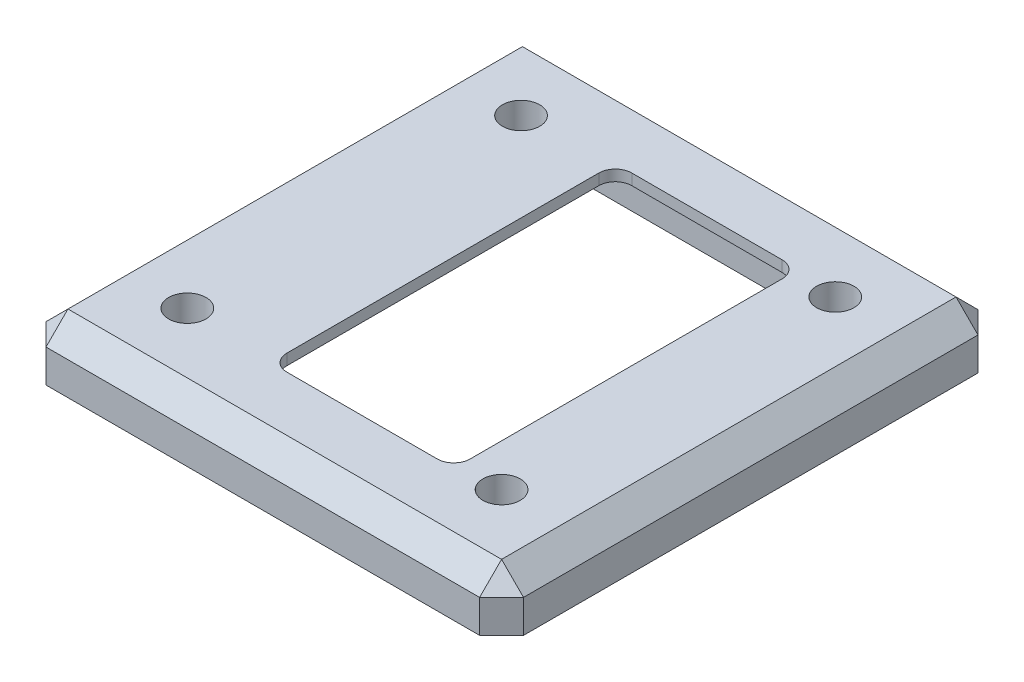
SolidWorks part; units mm, degrees
ref_plane "Спереди" through (0, 0, 0) normal (0, 0, 1) x (1, 0, 0)
ref_plane "Сверху" through (0, 0, 0) normal (0, 1, 0) x (1, 0, 0)
ref_plane "Справа" through (0, 0, 0) normal (1, 0, 0) x (0, 0, -1)
sketch "Эскиз2" plane through (0, 0, 0) normal (0, 1, 0) x (1, 0, 0)
  line L0 (-21.75, -7) -> (-21.75, -22.7)
  line L1 (-21.75, -22.7) -> (21.75, -22.7)
  line L2 (21.75, -22.7) -> (21.75, 22.7)
  line L3 (21.75, 22.7) -> (-21.75, 22.7)
  line L4 (-21.75, 22.7) -> (-21.75, 7)
  line L5 (-21.75, 11.7) -> (-21.75, -11.7)
  line L8 (16.75, 17.7) -> (-16.75, 17.7) construction
  line L9 (16.75, -17.7) -> (16.75, 17.7) construction
  line L10 (-16.75, -17.7) -> (16.75, -17.7) construction
  line L11 (-16.75, -7) -> (-16.75, -17.7) construction
  line L12 (-16.75, 17.7) -> (-16.75, 7) construction
  line L17 (-16.75, 11.7) -> (-16.75, -11.7) construction
  line L19 (16.75, 17.7) -> (-16.75, 17.7)
  line L20 (16.75, -17.7) -> (16.75, 17.7)
  line L21 (-16.75, -17.7) -> (16.75, -17.7)
  line L22 (-16.75, -7) -> (-16.75, -17.7)
  line L23 (-16.75, 17.7) -> (-16.75, 7)
  line L24 (-16.75, 11.7) -> (-16.75, -11.7)
  dimension "D1" = 5
extrude "Бобышка-Вытянуть2" add sketch "Эскиз2" along normal blind 5 contours L4 L5 L0 L1 L2 L3 L24 L23 L19 L20 L21 L22
sketch "Эскиз3" plane through (0, 5, 0) normal (0, 1, 0) x (1, 0, 0)
  line L0 (-13.0019, 12.7) -> (-15.75, 12.7) construction
  line L1 (-12.0019, -13.7) -> (-12.0019, -16.7) construction
  line L2 (-15.75, -12.7) -> (-13.0019, -12.7) construction
  line L3 (12.75, -12.7) -> (15.75, -12.7) construction
  line L4 (11.75, -16.7) -> (11.75, -13.7) construction
  line L5 (-16.75, -17.7) -> (16.75, -17.7) construction
  line L6 (16.75, -17.7) -> (16.75, 17.7) construction
  line L7 (15.75, 12.7) -> (12.75, 12.7) construction
  line L8 (11.75, 13.7) -> (11.75, 16.7) construction
  line L9 (-16.75, 17.7) -> (-16.75, -17.7) construction
  line L10 (16.75, 17.7) -> (-16.75, 17.7) construction
  line L11 (-12.0019, 16.7) -> (-12.0019, 13.7) construction
  line L12 (-12.0019, -13.7) -> (-12.0019, -16.7)
  line L13 (-15.75, -12.7) -> (-13.0019, -12.7)
  line L14 (12.75, -12.7) -> (15.75, -12.7)
  line L15 (11.75, -16.7) -> (11.75, -13.7)
  line L16 (-16.75, -17.7) -> (16.75, -17.7)
  line L17 (16.75, -17.7) -> (16.75, 17.7)
  line L18 (15.75, 12.7) -> (12.75, 12.7)
  line L19 (11.75, 13.7) -> (11.75, 16.7)
  line L20 (-16.75, 17.7) -> (-16.75, -17.7)
  line L21 (16.75, 17.7) -> (-16.75, 17.7)
  line L22 (-12.0019, 16.7) -> (-12.0019, 13.7)
  line L23 (-13.0019, 12.7) -> (-15.75, 12.7)
  line L24 (-12.0019, 16.7) -> (-12.0019, 17.7)
  line L25 (-15.75, 12.7) -> (-16.75, 12.7)
  line L26 (11.75, 16.7) -> (11.75, 17.7)
  line L27 (15.75, 12.7) -> (16.75, 12.7)
  line L28 (11.75, -16.7) -> (11.75, -17.7)
  line L29 (15.75, -12.7) -> (16.75, -12.7)
  line L30 (-15.75, -12.7) -> (-16.75, -12.7)
  line L31 (-12.0019, -16.7) -> (-12.0019, -17.7)
  arc A3 (-12.0019, -13.7) -> (-13.0019, -12.7) centre (-13.0019, -13.7) ccw construction
  arc A6 (12.75, -12.7) -> (11.75, -13.7) centre (12.75, -13.7) ccw construction
  arc A9 (11.75, 13.7) -> (12.75, 12.7) centre (12.75, 13.7) ccw construction
  arc A12 (-13.0019, 12.7) -> (-12.0019, 13.7) centre (-13.0019, 13.7) ccw construction
  arc A14 (-12.0019, -13.7) -> (-13.0019, -12.7) centre (-13.0019, -13.7) ccw
  arc A17 (12.75, -12.7) -> (11.75, -13.7) centre (12.75, -13.7) ccw
  arc A20 (11.75, 13.7) -> (12.75, 12.7) centre (12.75, 13.7) ccw
  arc A23 (-13.0019, 12.7) -> (-12.0019, 13.7) centre (-13.0019, 13.7) ccw
  line M5 (-16.75, -17.7) -> (-16.75, 17.7)
  line M6 (-16.75, 17.7) -> (16.75, 17.7)
  line M7 (16.75, 17.7) -> (16.75, -17.7)
  line M8 (16.75, -17.7) -> (-16.75, -17.7)
extrude "Бобышка-Вытянуть3" add sketch "Эскиз3" against normal up to surface (3.8 mm away) contours L23 A23 L22 L24 L20 L25 M6 | L19 A20 L18 L27 L26 M7 M6 | L14 A17 L15 L28 L29 M8 M7 | L12 A14 L13 L30 L31 M5 M8
sketch "Эскиз4" plane through (0, 5, 0) normal (0, 1, 0) x (1, 0, 0)
  line L0 (-16.75, -12.7) -> (-13.0019, -12.7) construction
  line L1 (-13.0019, 12.7) -> (-16.75, 12.7) construction
  line L2 (-16.75, 12.7) -> (-16.75, -12.7) construction
  line L3 (-16.75, -12.7) -> (-13.0019, -12.7)
  line L4 (-13.0019, 12.7) -> (-16.75, 12.7)
  line L5 (-16.75, 12.7) -> (-16.75, -12.7)
  line L7 (12.75, -12.7) -> (16.75, -12.7) construction
  line L8 (16.75, -12.7) -> (16.75, 12.7) construction
  line L9 (16.75, 12.7) -> (12.75, 12.7) construction
  line L10 (12.75, -12.7) -> (16.75, -12.7)
  line L11 (16.75, -12.7) -> (16.75, 12.7)
  line L12 (16.75, 12.7) -> (12.75, 12.7)
  line L14 (-12.0019, -13.7) -> (-12.0019, -17.7) construction
  line L15 (-12.0019, -17.7) -> (11.75, -17.7) construction
  line L16 (11.75, -17.7) -> (11.75, -13.7) construction
  line L17 (11.75, 13.7) -> (11.75, 17.7) construction
  line L18 (11.75, 17.7) -> (-12.0019, 17.7) construction
  line L19 (-12.0019, 17.7) -> (-12.0019, 13.7) construction
  line L20 (-12.0019, -13.7) -> (-12.0019, -17.7)
  line L21 (-12.0019, -17.7) -> (11.75, -17.7)
  line L22 (11.75, -17.7) -> (11.75, -13.7)
  line L23 (11.75, 13.7) -> (11.75, 17.7)
  line L24 (11.75, 17.7) -> (-12.0019, 17.7)
  line L25 (-12.0019, 17.7) -> (-12.0019, 13.7)
  line L26 (-4.8, -14.71) -> (8.9, -14.71) construction
  line L27 (9.4, -14.21) -> (9.4, 14.21) construction
  line L28 (8.9, 14.71) -> (-4.8, 14.71) construction
  line L29 (-5.3, 14.21) -> (-5.3, -14.21) construction
  line L30 (-4.8, -14.71) -> (8.9, -14.71) construction
  line L31 (9.4, -14.21) -> (9.4, 14.21) construction
  line L32 (8.9, 14.71) -> (-4.8, 14.71) construction
  line L33 (-5.3, 14.21) -> (-5.3, -14.21) construction
  line L34 (-4.8, -15.71) -> (8.9, -15.71)
  line L35 (10.4, -14.21) -> (10.4, 14.21)
  line L36 (8.9, 15.71) -> (-4.8, 15.71)
  line L37 (-6.3, 14.21) -> (-6.3, -14.21)
  arc A0 (11.75, 13.7) -> (12.75, 12.7) centre (12.75, 13.7) ccw construction
  arc A1 (12.75, -12.7) -> (11.75, -13.7) centre (12.75, -13.7) ccw construction
  arc A2 (-13.0019, 12.7) -> (-12.0019, 13.7) centre (-13.0019, 13.7) ccw construction
  arc A3 (-12.0019, -13.7) -> (-13.0019, -12.7) centre (-13.0019, -13.7) ccw construction
  arc A4 (11.75, 13.7) -> (12.75, 12.7) centre (12.75, 13.7) ccw
  arc A5 (12.75, -12.7) -> (11.75, -13.7) centre (12.75, -13.7) ccw
  arc A6 (-13.0019, 12.7) -> (-12.0019, 13.7) centre (-13.0019, 13.7) ccw
  arc A7 (-12.0019, -13.7) -> (-13.0019, -12.7) centre (-13.0019, -13.7) ccw
  arc A8 (8.9, -14.71) -> (9.4, -14.21) centre (8.9, -14.21) ccw construction
  arc A9 (-5.3, -14.21) -> (-4.8, -14.71) centre (-4.8, -14.21) ccw construction
  arc A10 (9.4, 14.21) -> (8.9, 14.71) centre (8.9, 14.21) ccw construction
  arc A11 (-4.8, 14.71) -> (-5.3, 14.21) centre (-4.8, 14.21) ccw construction
  arc A12 (8.9, -14.71) -> (9.4, -14.21) centre (8.9, -14.21) ccw construction
  arc A13 (-5.3, -14.21) -> (-4.8, -14.71) centre (-4.8, -14.21) ccw construction
  arc A14 (9.4, 14.21) -> (8.9, 14.71) centre (8.9, 14.21) ccw construction
  arc A15 (-4.8, 14.71) -> (-5.3, 14.21) centre (-4.8, 14.21) ccw construction
  arc A16 (-6.3, -14.21) -> (-4.8, -15.71) centre (-4.8, -14.21) ccw
  arc A17 (8.9, -15.71) -> (10.4, -14.21) centre (8.9, -14.21) ccw
  arc A18 (10.4, 14.21) -> (8.9, 15.71) centre (8.9, 14.21) ccw
  arc A19 (-4.8, 15.71) -> (-6.3, 14.21) centre (-4.8, 14.21) ccw
  dimension "D1" = 1
extrude "Бобышка-Вытянуть4" add sketch "Эскиз4" against normal blind 1
chamfer "Фаска1" distance 2 angle 45 8 edges at (0, 5, 22.7) (21.75, 2.5, 22.7) (21.75, 5, 0) (21.75, 2.5, -22.7) (0, 5, -22.7) (-21.75, 2.5, -22.7) (-21.75, 5, 0) (-21.75, 2.5, 22.7)
hole_wizard "Отверстие с зазором M31" positions "Эскиз6" profile "Эскиз7" hole size "M3" standard "DIN" end condition through all
sketch "Эскиз6" plane through (0, 5, 0) normal (0, 1, 0) x (1, 0, 0)
  circle A0 centre (14.25, -15.2) radius 1.7 construction
  circle A1 centre (14.25, 15.2) radius 1.7 construction
  circle A2 centre (-14.376, 15.2) radius 1.7 construction
  circle A3 centre (-14.376, -15.2) radius 1.7 construction
  circle A4 centre (14.25, -15.2) radius 1.7 construction
  circle A5 centre (14.25, 15.2) radius 1.7 construction
  circle A6 centre (-14.376, 15.2) radius 1.7 construction
  circle A7 centre (-14.376, -15.2) radius 1.7 construction
  point P1 (14.25, -15.2)
  point P3 (14.25, 15.2)
  point P5 (-14.376, 15.2)
  point P7 (-14.376, -15.2)
sketch "Эскиз7" plane through (14.25, 5, 15.2) normal (1, 0, 0) x (0, 0, 1)
  line L0 (0, 0) -> (0, 5)
  line L1 (0, 5) -> (1.7, 5)
  line L2 (1.7, 5) -> (1.7, 0)
  line L5 (1.7, 0) -> (0, 0)
  line L11 (0, -6.35) -> (0, 107.95) construction
  dimension "Диаметр сквозного отверстия" = 3.4
  dimension "Глубина сквозного отверстия" = 5
